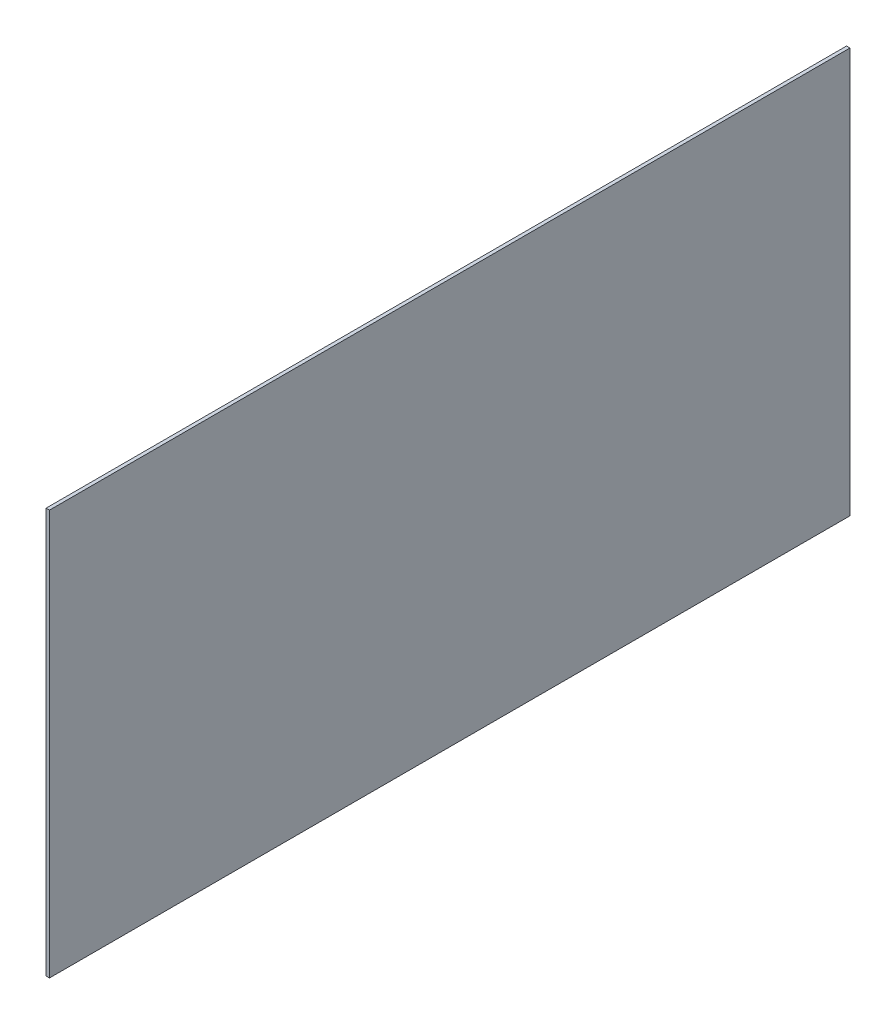
SolidWorks part; units mm, degrees
ref_plane "Front Plane" through (0, 0, 0) normal (0, 0, 1) x (1, 0, 0)
ref_plane "Top Plane" through (0, 0, 0) normal (0, 1, 0) x (1, 0, 0)
ref_plane "Right Plane" through (0, 0, 0) normal (1, 0, 0) x (0, 0, -1)
sketch "Sketch2" plane through (0, 0, 0) normal (1, 0, 0) x (0, 0, -1)
  line L1 (-121.6986, -281.826) -> (-472.1746, -281.826)
  line L2 (-121.6986, -281.826) -> (-121.6986, -104.426)
  line L3 (-121.6986, -104.426) -> (-472.1746, -104.426)
  line L4 (-472.1746, -281.826) -> (-472.1746, -104.426)
  line L5 (-121.6986, -281.826) -> (-472.1746, -104.426) construction
  line L6 (-121.6986, -104.426) -> (-472.1746, -281.826) construction
  line L9 (-121.6986, -281.826) -> (-121.6986, -104.426) construction
  point P0 (-296.9366, -193.126)
  point P5 (0, 0)
  point P7 (0, 0)
extrude "Boss-Extrude1" add sketch "Sketch2" along normal blind 1.5
